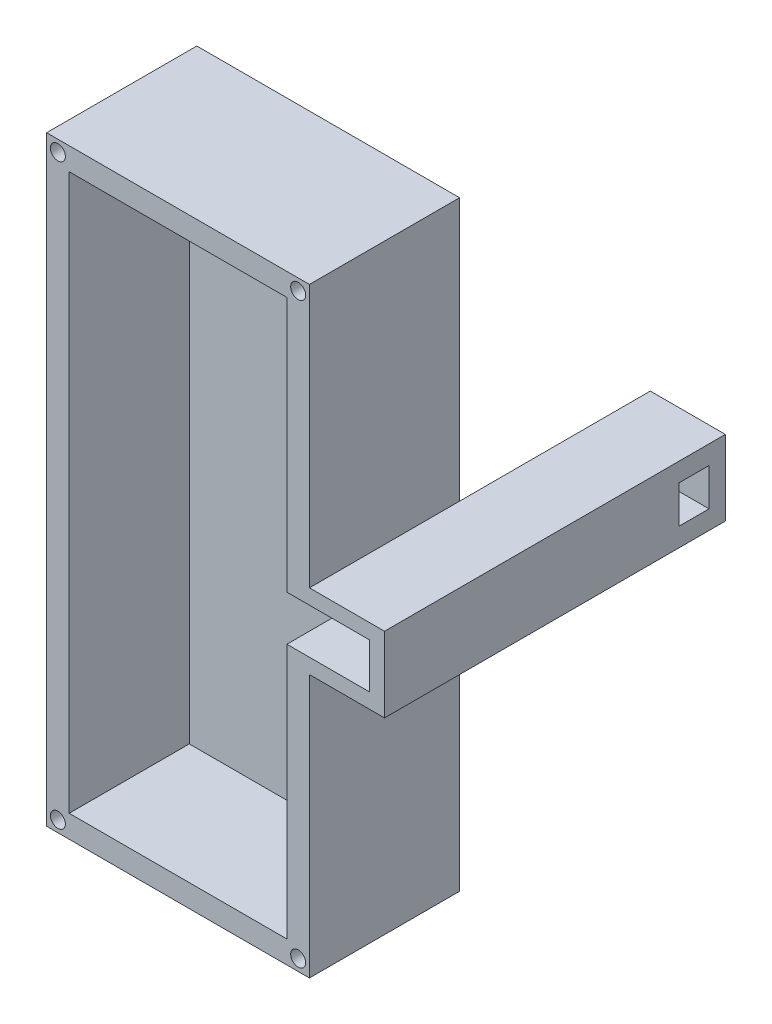
SolidWorks part; units mm, degrees
ref_plane "Front Plane" through (0, 0, 0) normal (0, 0, 1) x (1, 0, 0)
ref_plane "Top Plane" through (0, 0, 0) normal (0, 1, 0) x (1, 0, 0)
ref_plane "Right Plane" through (0, 0, 0) normal (1, 0, 0) x (0, 0, -1)
sketch "Sketch1" plane through (0, 0, 0) normal (0, 0, 1) x (1, 0, 0)
  line L1 (-17.5, -40) -> (17.5, -40)
  line L2 (-17.5, -40) -> (-17.5, 40)
  line L3 (-17.5, 40) -> (17.5, 40)
  line L4 (17.5, -40) -> (17.5, 40)
  line L5 (-17.5, -40) -> (17.5, 40) construction
  line L6 (-17.5, 40) -> (17.5, -40) construction
  point P0 (0, 0)
  dimension "D1" = 80
  dimension "D2" = 35
extrude "Boss-Extrude1" add sketch "Sketch1" along normal blind 20
sketch "Sketch2" plane through (17.5, 0, 0) normal (1, 0, 0) x (0, 0, -1)
  line L0 (0, -40) -> (0, 40) construction
  line L8 (0, 5) -> (25.4, 5)
  line L9 (0, -5) -> (25.4, -5)
  line L11 (25.4, -5) -> (25.4, 5)
  line L12 (0, 5) -> (-20, 5)
  line L13 (-20, -40) -> (-20, 40) construction
  line L14 (-20, 5) -> (-20, -5)
  line L15 (-20, -5) -> (0, -5)
  point P0 (0, 0)
  dimension "D3" = 25.4
  dimension "D4" = 25.4
extrude "Boss-Extrude2" add sketch "Sketch2" along normal blind 10 separate body
sketch "Sketch3" plane through (0, 0, 20) normal (0, 0, 1) x (1, 0, 0)
  line L1 (17.5, -5) -> (27.5, 5) construction
  line L4 (17.5, 5) -> (27.5, -5) construction
  line L14 (19.5, -3) -> (25.5, -3)
  line L15 (19.5, -3) -> (19.5, 3)
  line L16 (19.5, 3) -> (25.5, 3)
  line L17 (25.5, -3) -> (25.5, 3)
  line L18 (19.5, -3) -> (25.5, 3) construction
  line L19 (19.5, 3) -> (25.5, -3) construction
  point P2 (22.5, 0)
  dimension "D1" = 6
extrude "Cut-Extrude2" cut sketch "Sketch3" against normal blind 39.37
sketch "Sketch6" plane through (27.5, 0, 0) normal (1, 0, 0) x (0, 0, -1)
  line L3 (19.2304, -2.5) -> (23.2304, -2.5)
  line L10 (19.2304, -2.5) -> (19.2304, 2.5)
  line L11 (19.2304, 2.5) -> (23.2304, 2.5)
  line L12 (25.4, -5) -> (25.4, 5) construction
  line L13 (25.4, 0) -> (25.4, 2.5) construction
  line L14 (25.4, 0) -> (25.4, -2.5) construction
  line L15 (23.2304, -2.5) -> (23.2304, 2.5)
  line L16 (19.2304, -2.5) -> (23.2304, 2.5) construction
  line L17 (19.2304, 2.5) -> (23.2304, -2.5) construction
  point P5 (21.2304, 0)
  point P6 (21.2304, 0)
  dimension "D2" = 4
  dimension "D3" = 5
  dimension "D4" = 2.5
  dimension "D6" = 2.5
extrude "Cut-Extrude4" cut sketch "Sketch6" against normal blind 5
sketch "Sketch7" plane through (0, 0, 20) normal (0, 0, 1) x (1, 0, 0)
  line L0 (17.5, 40) -> (14.5, 40) construction
  line L1 (17.5, 40) -> (-17.5, 40) construction
  line L2 (14.5, 40) -> (14.5, 37) construction
  line L3 (14.5, 37) -> (14.5, -37)
  line L5 (-14.5, -37) -> (-14.5, 37)
  line L6 (-14.5, 37) -> (14.5, 37)
  line L7 (14.5, -37) -> (14.5, 37)
  line L10 (14.5, -37) -> (-14.5, -37)
  point P6 (0, 0)
  dimension "D1" = 3
  dimension "D2" = 3
  dimension "D3" = 74
  dimension "D4" = 29
extrude "Cut-Extrude5" cut sketch "Sketch7" against normal blind 16 contours L10 L3 L6 L5
sketch "Sketch9" plane through (0, -37, 0) normal (0, 1, 0) x (1, 0, 0)
  line L0 (-14.5, -20) -> (-14.5, -16) construction
  line L1 (-14.5, -4) -> (-14.5, -20) construction
  line L2 (-14.5, -4) -> (-14.5, -8) construction
  line L3 (0, 0) -> (0, -21.8298) construction
  line L4 (-14.5, -8) -> (1.5, -8)
  line L5 (-14.5, -8) -> (-14.5, -16)
  line L6 (-14.5, -16) -> (1.5, -16)
  line L7 (1.5, -8) -> (1.5, -16)
  line L9 (-1.5, -8) -> (-1.5, -16)
  line L12 (-1.5, -8) -> (14.5, -8)
  line L13 (14.5, -4) -> (14.5, -20) construction
  line L14 (14.5, -8) -> (14.5, -16)
  line L15 (14.5, -16) -> (-1.5, -16)
  dimension "D1" = 4
  dimension "D2" = 4
  dimension "D3" = 16
sketch "Sketch10" plane through (0, -37, 0) normal (0, 1, 0) x (1, 0, 0)
  line L0 (0, 0) -> (0, -26.8234) construction
sketch "Sketch11" plane through (0, 0, 20) normal (0, 0, 1) x (1, 0, 0)
  line L1 (19.5, 3) -> (32.0428, 3)
  line L2 (19.5, 3) -> (19.5, -3)
  line L3 (19.5, -3) -> (32.0428, -3)
  line L4 (32.0428, 3) -> (32.0428, -3)
extrude "Cut-Extrude8" cut sketch "Sketch11" against normal blind 16
sketch "Sketch12" plane through (0, -5, 0) normal (0, -1, 0) x (1, 0, 0)
  line L4 (26.5538, 0) -> (17.5, 0)
  line L5 (17.5, 0) -> (17.5, -4.5681)
  arc A0 (26.5538, 0) -> (17.5, -4.5681) centre (22.1671, -2.5619) cw
  point P10 (17.5, 0)
  dimension "D3" = 5.08
extrude "Boss-Extrude3" add sketch "Sketch12" against normal blind 10
fillet "Fillet5" radius 2.2 1 edges at (22.5, 0, -19.37)
sketch "Sketch13" plane through (0, 0, 0) normal (0, 0, -1) x (-1, 0, 0)
  line L0 (0, 0) -> (0, 40)
  line L1 (-17.5, 40) -> (17.5, 40) construction
  line L2 (0, 0) -> (0, -40)
  line L3 (17.5, -40) -> (-17.5, -40) construction
  line L4 (-63.1649, 0) -> (63.1649, 0) construction
  line L5 (-3.5, 11) -> (3.5, 11)
  line L6 (-3.5, 11) -> (-3.5, 29)
  line L7 (-3.5, 29) -> (3.5, 29)
  line L8 (3.5, 11) -> (3.5, 29)
  line L9 (-3.5, 11) -> (3.5, 29) construction
  line L10 (-3.5, 29) -> (3.5, 11) construction
  line L11 (-3.5, -29) -> (3.5, -29)
  line L12 (3.5, -11) -> (3.5, -29)
  line L13 (-3.5, -11) -> (3.5, -11)
  line L14 (-3.5, -11) -> (-3.5, -29)
  point P5 (0, 20)
  point P15 (0, 0)
  dimension "D1" = 7
  dimension "D2" = 18
extrude "Boss-Extrude4" add sketch "Sketch13" along normal blind 8 contours L7 L8 L5 L6 | L11 L12 L13 L14
sketch "Sketch14" plane through (3.5, 0, 0) normal (1, 0, 0) x (0, 0, -1)
  line L0 (8, 29) -> (4, 29)
  line L1 (8, 29) -> (0, 29) construction
  line L2 (4, 11) -> (4, 29)
  line L3 (8, 11) -> (0, 11) construction
  line L4 (3.0005, 13.7504) -> (5.0005, 13.7504)
  line L5 (3.0005, 13.7504) -> (3.0005, 26.2504)
  line L6 (3.0005, 26.2504) -> (5.0005, 26.2504)
  line L7 (5.0005, 13.7504) -> (5.0005, 26.2504)
  line L8 (3.0005, 13.7504) -> (5.0005, 26.2504) construction
  line L9 (3.0005, 26.2504) -> (5.0005, 13.7504) construction
  line L10 (4, 20) -> (8, 20)
  line L11 (8, 11) -> (8, 29) construction
  dimension "D1" = 12.5
  dimension "D2" = 2
extrude "Cut-Extrude9" cut sketch "Sketch14" against normal through all
sketch "Sketch15" plane through (3.5, 0, 0) normal (1, 0, 0) x (0, 0, -1)
  line L0 (8, -11) -> (4, -11)
  line L1 (8, -11) -> (0, -11) construction
  line L2 (4, -11) -> (4, -29)
  line L3 (8, -29) -> (0, -29) construction
  line L4 (3, -26.2501) -> (5, -26.2501)
  line L5 (3, -26.2501) -> (3, -13.7501)
  line L6 (3, -13.7501) -> (5, -13.7501)
  line L7 (5, -26.2501) -> (5, -13.7501)
  line L8 (3, -26.2501) -> (5, -13.7501) construction
  line L9 (3, -13.7501) -> (5, -26.2501) construction
  line L10 (4, -20) -> (8, -20)
  line L11 (8, -11) -> (8, -29) construction
  dimension "D1" = 12.5
  dimension "D2" = 2
extrude "Cut-Extrude10" cut sketch "Sketch15" against normal through all contours L7 L6 L5 L4
sketch "Sketch16" plane through (19.5, 0, 0) normal (1, 0, 0) x (0, 0, -1)
  line L1 (-20, 3) -> (-4, 3)
  line L2 (-20, 3) -> (-20, -3)
  line L3 (-20, -3) -> (-4, -3)
  line L4 (-4, 3) -> (-4, -3)
extrude "Cut-Extrude11" cut sketch "Sketch16" against normal blind 10
sketch "Sketch17" plane through (25.5, 0, 0) normal (-1, 0, 0) x (0, 0, 1)
  line L1 (4, 3) -> (20, 3)
  line L2 (4, 3) -> (4, -3)
  line L3 (4, -3) -> (20, -3)
  line L4 (20, 3) -> (20, -3)
extrude "Boss-Extrude5" add sketch "Sketch17" against normal blind 2
sketch "Sketch18" plane through (0, 0, 0) normal (0, 0, 1) x (1, 0, 0)
  line L1 (19.5, -3) -> (25.5, -3)
  line L2 (19.5, -3) -> (19.5, 3)
  line L3 (19.5, 3) -> (25.5, 3)
  line L4 (25.5, -3) -> (25.5, 3)
extrude "Cut-Extrude12" cut sketch "Sketch18" against normal blind 19
sketch "Sketch19" plane through (0, 0, 20) normal (0, 0, 1) x (1, 0, 0)
  circle A0 centre (16, 38.5) radius 1
  circle A1 centre (-16, 38.5) radius 1
  circle A2 centre (16, -38.5) radius 1
  circle A3 centre (-16, -38.5) radius 1
  dimension "D1" = 2
  dimension "D2" = 2
extrude "Cut-Extrude13" cut sketch "Sketch19" against normal blind 3
